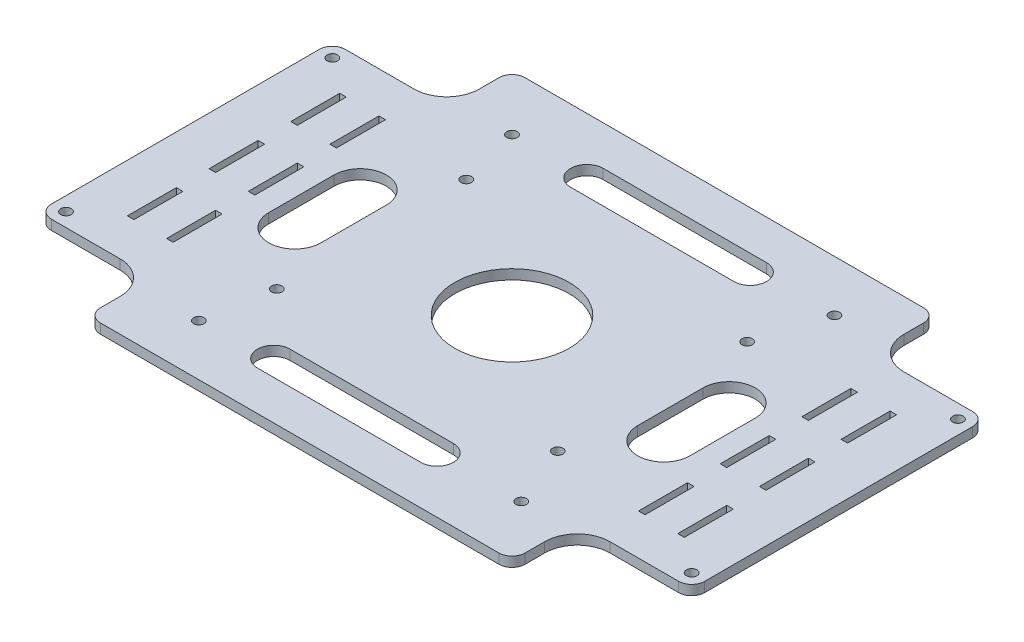
SolidWorks part; units mm, degrees
ref_plane "前视基准面" through (0, 0, 0) normal (0, 0, 1) x (1, 0, 0)
ref_plane "上视基准面" through (0, 0, 0) normal (0, 1, 0) x (1, 0, 0)
ref_plane "右视基准面" through (0, 0, 0) normal (1, 0, 0) x (0, 0, -1)
other "Configuration Table"
sketch "草图1" plane through (0, 0, 0) normal (0, 1, 0) x (1, 0, 0)
  line L4 (-65, 65) -> (65, 65)
  line L5 (-65, 65) -> (-65, 55)
  line L6 (65, 65) -> (65, 55)
  line L7 (-65, -65) -> (65, -65)
  line L8 (-65, 65) -> (65, -65) construction
  line L9 (65, 65) -> (-65, -65) construction
  line L10 (-50, 40) -> (50, 40) construction
  line L12 (50, 40) -> (50, -40) construction
  line L13 (-50, -40) -> (50, -40) construction
  line L14 (-50, 40) -> (50, -40) construction
  line L15 (50, 40) -> (-50, -40) construction
  line L16 (-47.93, 47.93) -> (47.93, 47.93) construction
  line L17 (-47.93, 47.93) -> (-47.93, -47.93) construction
  line L18 (47.93, 47.93) -> (47.93, -47.93) construction
  line L19 (-47.93, -47.93) -> (47.93, -47.93) construction
  line L20 (-47.93, 47.93) -> (47.93, -47.93) construction
  line L21 (47.93, 47.93) -> (-47.93, -47.93) construction
  line L22 (-100, 0) -> (-56.465, 0) construction
  line L23 (-56.465, 65) -> (-56.465, -65) construction
  line L24 (-78.2325, 0) -> (-78.2325, 45) construction
  line L29 (-78.2325, 0) -> (-84.2325, 0)
  line L30 (-83.2325, -7.5) -> (-85.2325, -7.5)
  line L31 (-83.2325, -7.5) -> (-83.2325, 7.5)
  line L57 (-49.965, 22) -> (-51.965, 22)
  line L59 (-49.965, 38) -> (-51.965, 38)
  line L132 (49.3442, 49.3442) -> (65, 65)
  line L133 (-100, 45) -> (-95.7574, 40.7574)
  line L145 (-56.465, -10) -> (-56.465, 10) construction
  line L153 (-56.465, 10) -> (-56.465, -10) construction
  line L154 (-48.465, 10) -> (-48.465, -10)
  line L155 (-64.465, 10) -> (-64.465, -10)
  line L156 (56.465, 10) -> (56.465, -10) construction
  line L157 (48.465, 10) -> (48.465, -10)
  line L158 (64.465, 10) -> (64.465, -10)
  line L166 (-85.2325, -7.5) -> (-85.2325, 7.5)
  line L168 (-83.2325, 7.5) -> (-85.2325, 7.5)
  line L171 (-83.2325, -7.5) -> (-85.2325, 7.5) construction
  line L172 (-85.2325, -7.5) -> (-83.2325, 7.5) construction
  line L193 (-25, 47.93) -> (25, 47.93) construction
  line L194 (-25, -47.93) -> (25, -47.93) construction
  line L195 (-25, 52.93) -> (25, 52.93)
  line L196 (-25, 42.93) -> (25, 42.93)
  line L197 (-25, -52.93) -> (25, -52.93)
  line L198 (-25, -42.93) -> (25, -42.93)
  line L199 (43, -29) -> (-43, -29) construction
  line L200 (43, -29) -> (43, 29) construction
  line L201 (-43, -29) -> (-43, 29) construction
  line L202 (43, 29) -> (-43, 29) construction
  line L203 (43, -29) -> (-43, 29) construction
  line L204 (-43, -29) -> (43, 29) construction
  line L205 (100, -45) -> (75, -45)
  line L206 (100, -45) -> (100, 45)
  line L207 (-100, -45) -> (-100, 45)
  line L208 (100, 45) -> (75, 45)
  line L209 (100, -45) -> (-100, 45) construction
  line L210 (-100, -45) -> (100, 45) construction
  line L211 (65, -55) -> (65, -65)
  line L212 (-65, -55) -> (-65, -65)
  line L213 (47.93, -45) -> (-56.465, -45) construction
  line L214 (-75, -45) -> (-100, -45)
  line L215 (-75, 45) -> (-100, 45)
  line L216 (47.93, 45) -> (-47.93, 45) construction
  line L217 (-71.2325, -7.5) -> (-71.2325, 7.5)
  line L218 (-73.2325, 7.5) -> (-71.2325, 7.5)
  line L219 (-73.2325, -7.5) -> (-73.2325, 7.5)
  line L220 (-73.2325, -7.5) -> (-71.2325, -7.5)
  line L221 (-83.2325, -32.5) -> (-85.2325, -32.5)
  line L222 (-83.2325, -32.5) -> (-83.2325, -17.5)
  line L223 (-83.2325, -17.5) -> (-85.2325, -17.5)
  line L224 (-85.2325, -32.5) -> (-85.2325, -17.5)
  line L225 (-71.2325, -32.5) -> (-71.2325, -17.5)
  line L226 (-73.2325, -17.5) -> (-71.2325, -17.5)
  line L227 (-73.2325, -32.5) -> (-73.2325, -17.5)
  line L228 (-73.2325, -32.5) -> (-71.2325, -32.5)
  line L229 (-71.2325, 17.5) -> (-71.2325, 32.5)
  line L230 (-73.2325, 32.5) -> (-71.2325, 32.5)
  line L231 (-73.2325, 17.5) -> (-73.2325, 32.5)
  line L232 (-73.2325, 17.5) -> (-71.2325, 17.5)
  line L233 (-83.2325, 17.5) -> (-85.2325, 17.5)
  line L234 (-83.2325, 17.5) -> (-83.2325, 32.5)
  line L235 (-83.2325, 32.5) -> (-85.2325, 32.5)
  line L236 (-85.2325, 17.5) -> (-85.2325, 32.5)
  line L237 (0, 0) -> (0, 47.93)
  line L238 (83.2325, 17.5) -> (83.2325, 32.5)
  line L239 (83.2325, 32.5) -> (85.2325, 32.5)
  line L240 (85.2325, 17.5) -> (85.2325, 32.5)
  line L241 (83.2325, 17.5) -> (85.2325, 17.5)
  line L242 (73.2325, 17.5) -> (71.2325, 17.5)
  line L243 (73.2325, 17.5) -> (73.2325, 32.5)
  line L244 (73.2325, 32.5) -> (71.2325, 32.5)
  line L245 (71.2325, 17.5) -> (71.2325, 32.5)
  line L246 (85.2325, -7.5) -> (85.2325, 7.5)
  line L247 (83.2325, 7.5) -> (85.2325, 7.5)
  line L248 (83.2325, -7.5) -> (83.2325, 7.5)
  line L249 (83.2325, -7.5) -> (85.2325, -7.5)
  line L250 (73.2325, -7.5) -> (71.2325, -7.5)
  line L251 (73.2325, -7.5) -> (73.2325, 7.5)
  line L252 (73.2325, 7.5) -> (71.2325, 7.5)
  line L253 (71.2325, -7.5) -> (71.2325, 7.5)
  line L254 (83.2325, -32.5) -> (83.2325, -17.5)
  line L255 (83.2325, -17.5) -> (85.2325, -17.5)
  line L256 (85.2325, -32.5) -> (85.2325, -17.5)
  line L257 (83.2325, -32.5) -> (85.2325, -32.5)
  line L258 (73.2325, -32.5) -> (71.2325, -32.5)
  line L259 (73.2325, -32.5) -> (73.2325, -17.5)
  line L260 (73.2325, -17.5) -> (71.2325, -17.5)
  line L261 (71.2325, -32.5) -> (71.2325, -17.5)
  circle A0 centre (-47.93, 47.93) radius 1.6
  circle A1 centre (49.3442, 49.3442) radius 1.6
  circle A2 centre (50.7584, -47.93) radius 1.6
  circle A3 centre (-46.5158, -49.3442) radius 1.6
  arc A12 (-25, 52.93) -> (-25, 42.93) centre (-25, 47.93) ccw
  arc A13 (25, 42.93) -> (25, 52.93) centre (25, 47.93) ccw
  arc A14 (-25, -52.93) -> (-25, -42.93) centre (-25, -47.93) cw
  arc A15 (25, -42.93) -> (25, -52.93) centre (25, -47.93) cw
  circle A16 centre (43, -29) radius 1.6
  circle A17 centre (-43, -29) radius 1.6
  circle A18 centre (-43, 29) radius 1.6
  circle A19 centre (43, 29) radius 1.6
  arc A20 (65, 55) -> (75, 45) centre (75, 55) ccw
  arc A21 (-65, 55) -> (-75, 45) centre (-75, 55) cw
  arc A22 (-75, -45) -> (-65, -55) centre (-75, -55) cw
  arc A23 (75, -45) -> (65, -55) centre (75, -55) ccw
  circle A24 centre (0, 0) radius 12.5 construction
  circle A25 centre (0, 0) radius 17.5
  circle A26 centre (-95.7574, 40.7574) radius 1.6
  circle A27 centre (95.7574, 40.7574) radius 1.6
  circle A28 centre (95.7574, -40.7574) radius 1.6
  circle A29 centre (-95.7574, -40.7574) radius 1.6
  arc A30 (-48.465, 10) -> (-64.465, 10) centre (-56.465, 10) ccw
  arc A31 (-64.465, -10) -> (-48.465, -10) centre (-56.465, -10) ccw
  arc A32 (48.465, 10) -> (64.465, 10) centre (56.465, 10) cw
  arc A33 (64.465, -10) -> (48.465, -10) centre (56.465, -10) cw
  point P1 (0, 0)
  point P2 (0, 0)
  point P3 (0, 0)
  point P27 (1.4142, 0)
  point P30 (-56.465, 0)
  point P62 (0, 47.93)
  point P67 (0, -47.93)
  point P73 (0, 0)
  point P78 (0, 0)
  point P122 (-65, 45)
  point P125 (-65, -45)
  point P131 (0, 0)
  point P133 (47.93, 47.93)
  point P143 (-56.465, 0)
  point P150 (56.465, 0)
  point P160 (0, 0)
  point P164 (-56.465, 0)
  point P167 (-56.465, 10)
  dimension "D7" = 3.2
  dimension "D15" = 35
  dimension "D18" = 3.2
  dimension "D19" = 3.2
  dimension "D20" = 3.2
  dimension "D21" = 3.2
  dimension "D24" = 10
  dimension "D14" = 25
  dimension "D17" = 10
  dimension "D28" = 6
  dimension "D29" = 3.2
  dimension "D1" = 130
  dimension "D2" = 130
  dimension "D3" = 100
  dimension "D4" = 80
  dimension "D5" = 95.86
  dimension "D6" = 95.86
  dimension "D9" = 6
  dimension "D10" = 2
  dimension "D11" = 15
  dimension "D12" = 2
  dimension "D16" = 86
  dimension "D22" = 200
  dimension "D23" = 90
  dimension "D25" = 86
  dimension "D26" = 58
  dimension "D13" = 2
  dimension "D8" = 4
extrude "凸台-拉伸1" add sketch "草图1" along normal blind 3
fillet "圆角2" radius 4 8 edges at (100, 1.5, -45) (65, 1.5, -65) (-65, 1.5, -65) (-100, 1.5, -45) (-100, 1.5, 45) (-65, 1.5, 65) (65, 1.5, 65) (100, 1.5, 45)
